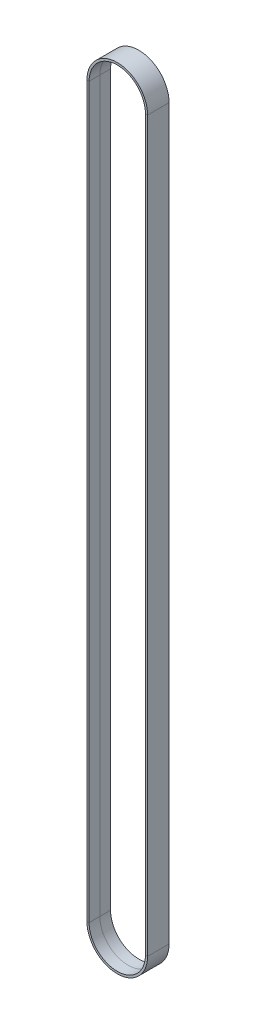
SolidWorks part; units mm, degrees
ref_plane "Спереди" through (0, 0, 0) normal (0, 0, 1) x (1, 0, 0)
ref_plane "Сверху" through (0, 0, 0) normal (0, 1, 0) x (1, 0, 0)
ref_plane "Справа" through (0, 0, 0) normal (1, 0, 0) x (0, 0, -1)
sketch "Эскиз2" plane through (0, 0, 0) normal (0, 0, 1) x (1, 0, 0)
  line L0 (0, 0) -> (1, 0) construction
  line L1 (0, 0) -> (0, 1) construction
  line L2 (26.25, 0) -> (26.25, -678.6787)
  line L3 (-26.25, -678.6787) -> (-26.25, 0)
  arc A0 (-26.25, 0) -> (26.25, 0) centre (0, 0) cw
  arc A1 (26.25, -678.6787) -> (-26.25, -678.6787) centre (0, -678.6787) cw
ref_plane "Плоскость1" through (0, 0, 0) normal (0, 0, 1) x (1, 0, 0)
sketch "Эскиз3" plane through (0, 0, 0) normal (0, 0, 1) x (1, 0, 0)
  line L0 (-26.25, -678.6787) -> (-26.25, 0) construction
  line L1 (26.25, 0) -> (26.25, -678.6787) construction
  line L2 (-26.25, -678.6787) -> (-26.25, 0)
  line L3 (26.25, 0) -> (26.25, -678.6787)
  arc A0 (26.25, 0) -> (-26.25, 0) centre (0, 0) ccw construction
  arc A1 (-26.25, -678.6787) -> (26.25, -678.6787) centre (0, -678.6787) ccw construction
  arc A2 (26.25, 0) -> (-26.25, 0) centre (0, 0) ccw
  arc A3 (-26.25, -678.6787) -> (26.25, -678.6787) centre (0, -678.6787) ccw
ref_plane "Плоскость2" through (0, 0, 0) normal (0, 1, 0) x (1, 0, 0)
sketch "Эскиз4" plane through (0, 0, 0) normal (0, 1, 0) x (1, 0, 0)
  line L0 (-24.7619, 10) -> (-21.1884, 10) construction
  line L2 (26.25, 0) -> (26.25, -10)
  line L3 (26.25, -10) -> (28.25, -10)
  line L6 (26.25, 0) -> (26.25, 10)
  line L7 (26.25, 10) -> (28.25, 10)
  line L9 (-21.1884, -10) -> (-24.7619, -10) construction
  line L10 (28.25, -10) -> (28.25, 10)
  dimension "D1" = 2
  dimension "D2" = 2
sweep "По траектории1" add profiles "Эскиз4" path "Эскиз3"
